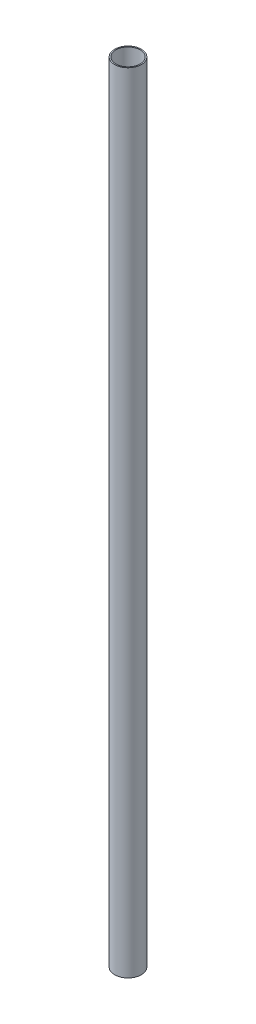
SolidWorks part; units mm, degrees
ref_plane "Front Plane" through (0, 0, 0) normal (0, 0, 1) x (1, 0, 0)
ref_plane "Top Plane" through (0, 0, 0) normal (0, 1, 0) x (1, 0, 0)
ref_plane "Right Plane" through (0, 0, 0) normal (1, 0, 0) x (0, 0, -1)
sketch "Sketch1" plane through (0, 0, 0) normal (0, 1, 0) x (1, 0, 0)
  circle A0 centre (0, 0) radius 98.5
  circle A1 centre (0, 0) radius 90
  dimension "D1" = 197
  dimension "D2" = 180
extrude "Rocket Shell" add sketch "Sketch1" along normal blind 5822
sketch "Sketch2" plane through (0, 0, 0) normal (0, -1, 0) x (1, 0, 0)
  circle A0 centre (0, 0) radius 90
  circle A1 centre (0, 0) radius 50
  dimension "D1" = 100
extrude "Solid Fuel" add sketch "Sketch2" against normal blind 1673 separate body
sketch "Sketch3" plane through (0, 1673, 0) normal (0, 1, 0) x (1, 0, 0)
  circle A0 centre (0, 0) radius 90
extrude "Liquid Fuel" add sketch "Sketch3" along normal blind 2900 separate body
sketch "Sketch4" plane through (0, 1673, 0) normal (0, -1, 0) x (1, 0, 0)
  circle A0 centre (0, 0) radius 90
extrude "Cut Core Out" cut sketch "Sketch4" against normal blind 400
